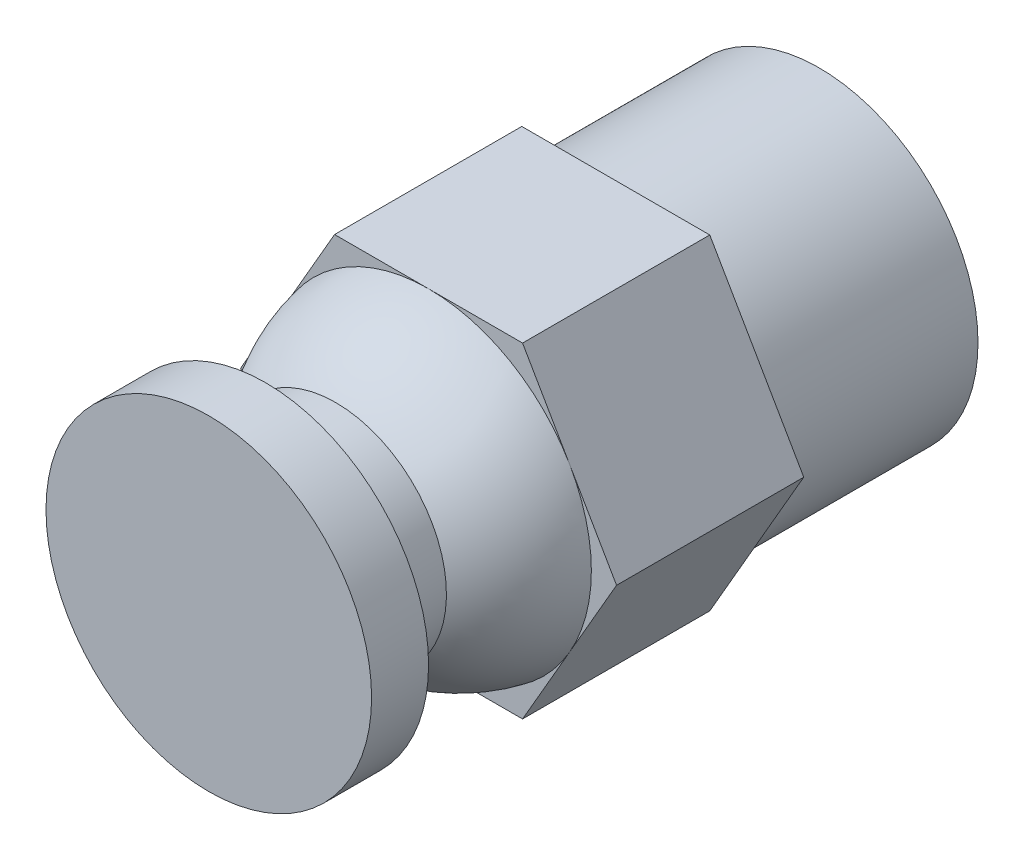
SolidWorks part; units mm, degrees
ref_plane "Front Plane" through (0, 0, 0) normal (0, 0, 1) x (1, 0, 0)
ref_plane "Top Plane" through (0, 0, 0) normal (0, 1, 0) x (1, 0, 0)
ref_plane "Right Plane" through (0, 0, 0) normal (1, 0, 0) x (0, 0, -1)
sketch "Sketch1" plane through (0, 0, 0) normal (0, 0, 1) x (1, 0, 0)
  circle A0 centre (0, 0) radius 4.875
  dimension "D1" = 9.75
extrude "Boss-Extrude1" add sketch "Sketch1" along normal blind 6.25
sketch "Sketch2" plane through (0, 0, 6.25) normal (0, 0, 1) x (1, 0, 0)
  line L1 (5.7735, 0) -> (2.8868, 5)
  line L2 (2.8868, 5) -> (-2.8868, 5)
  line L3 (-2.8868, 5) -> (-5.7735, 0)
  line L4 (-5.7735, 0) -> (-2.8868, -5)
  line L5 (-2.8868, -5) -> (2.8868, -5)
  line L6 (2.8868, -5) -> (5.7735, 0)
  circle A0 centre (0, 0) radius 5 construction
  point P1 (0, 0)
  dimension "D1" = 10
extrude "Boss-Extrude2" add sketch "Sketch2" along normal blind 5.75
sketch "Sketch3" plane through (0, 0, 12) normal (0, 0, 1) x (1, 0, 0)
  circle A0 centre (0, 0) radius 5
  dimension "D1" = 10
extrude "Boss-Extrude3" add sketch "Sketch3" along normal blind 6.75
sketch "Sketch4" plane through (0, 0, 0) normal (1, 0, 0) x (0, 0, -1)
  line L0 (-12, 0) -> (-17.0724, 0) construction
  line L1 (-12, 2.5) -> (-12, -2.5) construction
  line L2 (-17, 5) -> (-17, 3.4)
  line L3 (-12, 5) -> (-18.75, 5) construction
  line L4 (-17, 3.4) -> (-14.851, 3.4)
  line L5 (-17, 5) -> (-12, 5)
  arc A0 (-12, 5) -> (-14.851, 3.4) centre (-11.0684, 0) ccw
  point P12 (0, 0)
  dimension "D1" = 5.0861
  dimension "D2" = 5
  dimension "D3" = 1.6
revolve "Cut-Revolve1" cut sketch "Sketch4" angle 360 about L0
